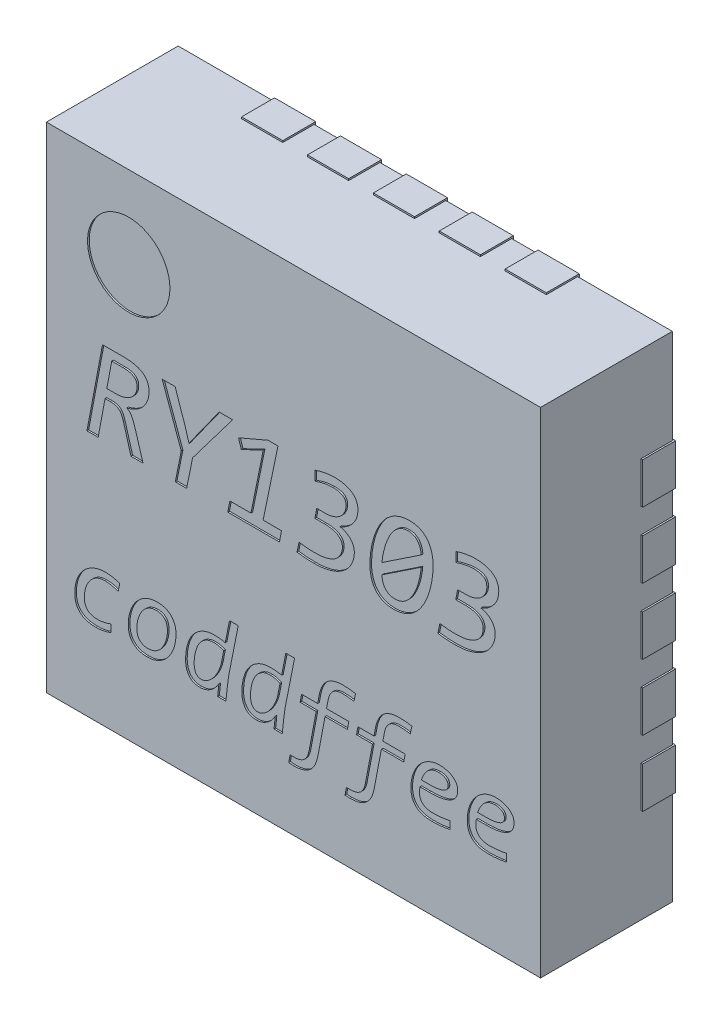
SolidWorks part; units mm, degrees
material "1023 碳钢板 (SS)"
ref_plane "前视基准面" through (0, 0, 0) normal (0, 0, 1) x (1, 0, 0)
ref_plane "上视基准面" through (0, 0, 0) normal (0, 1, 0) x (1, 0, 0)
ref_plane "右视基准面" through (0, 0, 0) normal (1, 0, 0) x (0, 0, -1)
ref_plane "芯片基底面" through (0, 0, 0.01) normal (0, 0, 1) x (1, 0, 0)
sketch "草图1" plane through (0, 0, 0.01) normal (0, 0, 1) x (1, 0, 0)
  line L1 (-1.5, 1.5) -> (1.5, 1.5)
  line L2 (-1.5, 1.5) -> (-1.5, -1.5)
  line L3 (-1.5, -1.5) -> (1.5, -1.5)
  line L4 (1.5, 1.5) -> (1.5, -1.5)
  line L5 (-1.5, 1.5) -> (1.5, -1.5) construction
  line L6 (-1.5, -1.5) -> (1.5, 1.5) construction
  point P0 (0, 0)
extrude "凸台-拉伸1" add sketch "草图1" along normal blind 0.8
sketch "草图3" plane through (0, 0, 0) normal (0, 0, 1) x (1, 0, 0)
  line L0 (0.525, 1.2) -> (0.275, 1.2)
  line L1 (0.525, 1.2) -> (0.525, 1.51)
  line L2 (0.925, 1.2) -> (0.675, 1.2)
  line L3 (0.925, 1.2) -> (0.925, 1.51)
  line L4 (0.925, 1.51) -> (0.675, 1.51)
  line L5 (0.675, 1.51) -> (0.675, 1.2)
  line L6 (0.525, 1.51) -> (0.275, 1.51)
  line L7 (0.275, 1.51) -> (0.275, 1.2)
  line L12 (0.125, 1.2) -> (-0.125, 1.2)
  line L13 (0.125, 1.2) -> (0.125, 1.51)
  line L14 (0.125, 1.51) -> (-0.125, 1.51)
  line L15 (-0.125, 1.51) -> (-0.125, 1.2)
  line L16 (-0.275, 1.2) -> (-0.525, 1.2)
  line L17 (-0.275, 1.2) -> (-0.275, 1.51)
  line L18 (-0.275, 1.51) -> (-0.525, 1.51)
  line L19 (-0.525, 1.51) -> (-0.525, 1.2)
  line L20 (-0.675, 1.2) -> (-0.925, 1.2)
  line L21 (-0.675, 1.2) -> (-0.675, 1.51)
  line L22 (-0.675, 1.51) -> (-0.925, 1.51)
  line L23 (-0.925, 1.51) -> (-0.925, 1.2)
  line L24 (1.2, -0.525) -> (1.2, -0.275)
  line L25 (1.2, -0.525) -> (1.51, -0.525)
  line L26 (1.2, -0.925) -> (1.2, -0.675)
  line L27 (1.2, -0.925) -> (1.51, -0.925)
  line L28 (1.51, -0.925) -> (1.51, -0.675)
  line L29 (1.51, -0.675) -> (1.2, -0.675)
  line L30 (1.51, -0.525) -> (1.51, -0.275)
  line L31 (1.51, -0.275) -> (1.2, -0.275)
  line L32 (1.2, -0.125) -> (1.2, 0.125)
  line L33 (1.2, -0.125) -> (1.51, -0.125)
  line L34 (1.51, -0.125) -> (1.51, 0.125)
  line L35 (1.51, 0.125) -> (1.2, 0.125)
  line L36 (1.2, 0.275) -> (1.2, 0.525)
  line L37 (1.2, 0.275) -> (1.51, 0.275)
  line L38 (1.51, 0.275) -> (1.51, 0.525)
  line L39 (1.51, 0.525) -> (1.2, 0.525)
  line L40 (1.2, 0.675) -> (1.2, 0.925)
  line L41 (1.2, 0.675) -> (1.51, 0.675)
  line L42 (1.51, 0.675) -> (1.51, 0.925)
  line L43 (1.51, 0.925) -> (1.2, 0.925)
  line L44 (-0.525, -1.2) -> (-0.275, -1.2)
  line L45 (-0.525, -1.2) -> (-0.525, -1.51)
  line L46 (-0.925, -1.2) -> (-0.675, -1.2)
  line L47 (-0.925, -1.2) -> (-0.925, -1.51)
  line L48 (-0.925, -1.51) -> (-0.675, -1.51)
  line L49 (-0.675, -1.51) -> (-0.675, -1.2)
  line L50 (-0.525, -1.51) -> (-0.275, -1.51)
  line L51 (-0.275, -1.51) -> (-0.275, -1.2)
  line L52 (-0.125, -1.2) -> (0.125, -1.2)
  line L53 (-0.125, -1.2) -> (-0.125, -1.51)
  line L54 (-0.125, -1.51) -> (0.125, -1.51)
  line L55 (0.125, -1.51) -> (0.125, -1.2)
  line L56 (0.275, -1.2) -> (0.525, -1.2)
  line L57 (0.275, -1.2) -> (0.275, -1.51)
  line L58 (0.275, -1.51) -> (0.525, -1.51)
  line L59 (0.525, -1.51) -> (0.525, -1.2)
  line L60 (0.675, -1.2) -> (0.925, -1.2)
  line L61 (0.675, -1.2) -> (0.675, -1.51)
  line L62 (0.675, -1.51) -> (0.925, -1.51)
  line L63 (0.925, -1.51) -> (0.925, -1.2)
  line L64 (-1.2, 0.525) -> (-1.2, 0.275)
  line L65 (-1.2, 0.525) -> (-1.51, 0.525)
  line L66 (-1.2, 0.925) -> (-1.2, 0.675)
  line L67 (-1.2, 0.925) -> (-1.51, 0.925)
  line L68 (-1.51, 0.925) -> (-1.51, 0.675)
  line L69 (-1.51, 0.675) -> (-1.2, 0.675)
  line L70 (-1.51, 0.525) -> (-1.51, 0.275)
  line L71 (-1.51, 0.275) -> (-1.2, 0.275)
  line L72 (-1.2, 0.125) -> (-1.2, -0.125)
  line L73 (-1.2, 0.125) -> (-1.51, 0.125)
  line L74 (-1.51, 0.125) -> (-1.51, -0.125)
  line L75 (-1.51, -0.125) -> (-1.2, -0.125)
  line L76 (-1.2, -0.275) -> (-1.2, -0.525)
  line L77 (-1.2, -0.275) -> (-1.51, -0.275)
  line L78 (-1.51, -0.275) -> (-1.51, -0.525)
  line L79 (-1.51, -0.525) -> (-1.2, -0.525)
  line L80 (-1.2, -0.675) -> (-1.2, -0.925)
  line L81 (-1.2, -0.675) -> (-1.51, -0.675)
  line L82 (-1.51, -0.675) -> (-1.51, -0.925)
  line L83 (-1.51, -0.925) -> (-1.2, -0.925)
  point P5 (0.8, 1.2)
  point P8 (0.4, 1.2)
  point P13 (0, 1.2)
  point P18 (-0.4, 1.2)
  point P23 (-0.8, 1.2)
  point P32 (1.2, -0.8)
  point P35 (1.2, -0.4)
  point P40 (1.2, 0)
  point P45 (1.2, 0.4)
  point P50 (1.2, 0.8)
  point P57 (-0.8, -1.2)
  point P60 (-0.4, -1.2)
  point P65 (0, -1.2)
  point P70 (0.4, -1.2)
  point P75 (0.8, -1.2)
  point P82 (-1.2, 0.8)
  point P85 (-1.2, 0.4)
  point P90 (-1.2, 0)
  point P95 (-1.2, -0.4)
  point P100 (-1.2, -0.8)
  point P103 (0, 0)
  dimension "D1" = 5
  dimension "D2" = 4
extrude "凸台-拉伸2" add sketch "草图3" along normal blind 0.2
sketch "草图4" plane through (0, 0, 0) normal (0, 0, 1) x (1, 0, 0)
  line L0 (-0.6, 0.9) -> (-0.9, 0.6)
  line L1 (0.9, 0.9) -> (-0.6, 0.9)
  line L2 (0.9, 0.9) -> (0.9, -0.9)
  line L3 (0.9, -0.9) -> (-0.9, -0.9)
  line L4 (-0.9, 0.6) -> (-0.9, -0.9)
  point P0 (0, 0)
extrude "凸台-拉伸3" add sketch "草图4" along normal blind 0.01
sketch "草图5" plane through (0, 0, 0.81) normal (0, 0, 1) x (1, 0, 0)
  line L0 (-1.5, 0) -> (1.5, 0) construction
  line L2 (-1.5, 1.5) -> (-1.5, -1.5) construction
  line L3 (1.5, -1.5) -> (1.5, 1.5) construction
  line L5 (-1.5, -1) -> (1.5, -1) construction
  circle A0 centre (-1, 1) radius 0.25
  text T0 "<i>RY1303</i>" font "Consolas" height 0.5
  text T1 "<i>coddffee</i>" font "Consolas" height 0.4
  point P13 (0, -1)
extrude "切除-拉伸1" cut sketch "草图5" against normal blind 0.01
